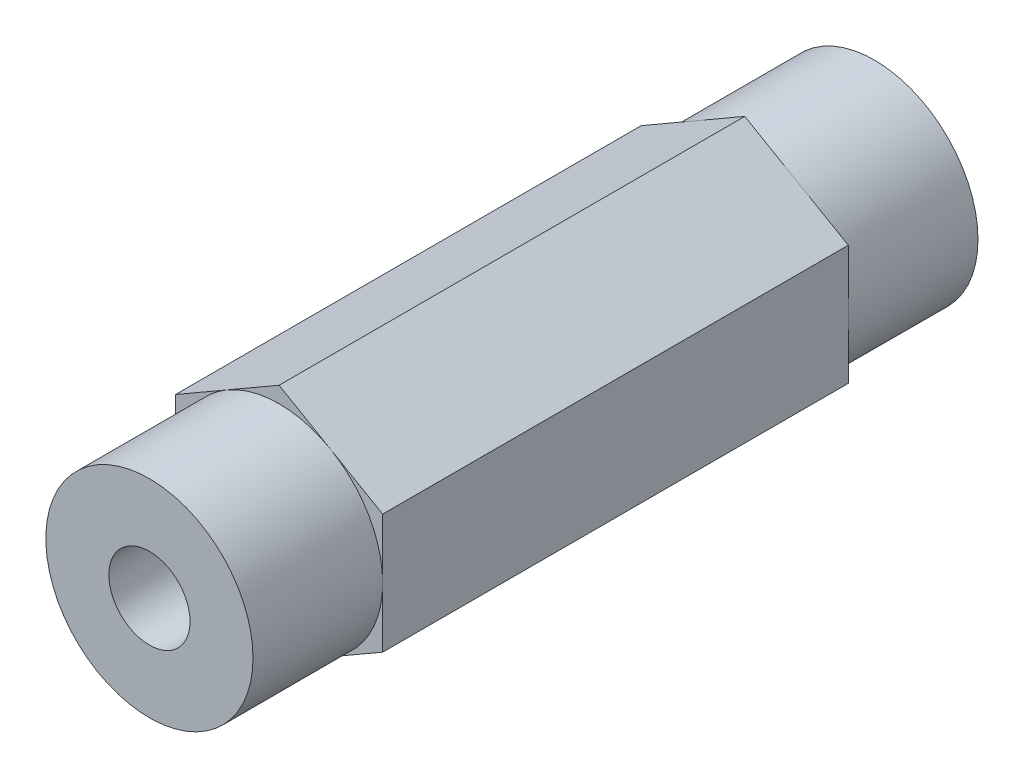
SolidWorks part; units mm, degrees
ref_plane "Front Plane" through (0, 0, 0) normal (0, 0, 1) x (1, 0, 0)
ref_plane "Top Plane" through (0, 0, 0) normal (0, 1, 0) x (1, 0, 0)
ref_plane "Right Plane" through (0, 0, 0) normal (1, 0, 0) x (0, 0, -1)
sketch "Sketch1" plane through (0, 0, 0) normal (0, 0, 1) x (1, 0, 0)
  line L1 (0, 7.3323) -> (-6.35, 3.6662)
  line L2 (-6.35, 3.6662) -> (-6.35, -3.6662)
  line L3 (-6.35, -3.6662) -> (0, -7.3323)
  line L4 (0, -7.3323) -> (6.35, -3.6662)
  line L5 (6.35, -3.6662) -> (6.35, 3.6662)
  line L6 (6.35, 3.6662) -> (0, 7.3323)
  circle A0 centre (0, 0) radius 6.35 construction
  dimension "D1" = 12.7
extrude "Boss-Extrude1" add sketch "Sketch1" along normal mid plane 28.5496
sketch "Sketch2" plane through (0, 0, 14.2748) normal (0, 0, 1) x (1, 0, 0)
  circle A0 centre (0, 0) radius 6.35
  circle A1 centre (0, 0) radius 2.4892
  dimension "D1" = 12.7
  dimension "D2" = 4.9784
extrude "Boss-Extrude2" add sketch "Sketch2" along normal blind 7.9502
mirror "Mirror1" about plane through (0, 0, 0) normal (0, 0, 1) of "Boss-Extrude2"
